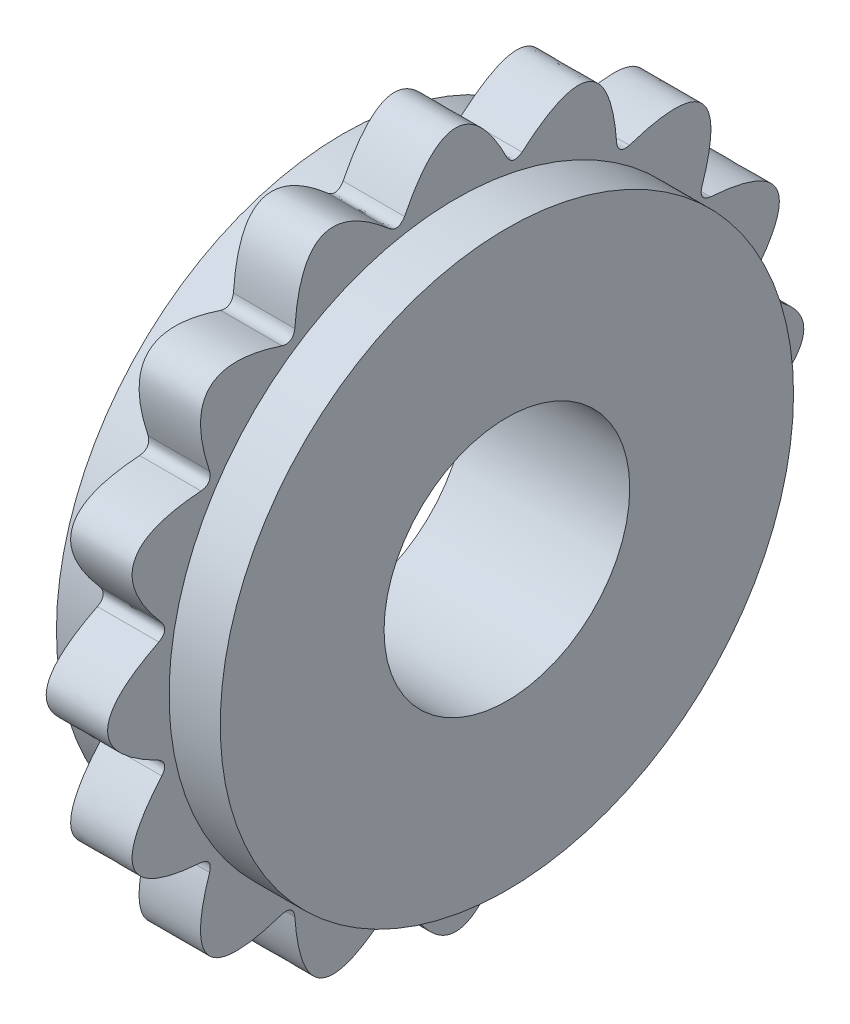
SolidWorks part; units mm, degrees
ref_plane "Front Plane" through (0, 0, 0) normal (0, 0, 1) x (1, 0, 0)
ref_plane "Top Plane" through (0, 0, 0) normal (0, 1, 0) x (1, 0, 0)
ref_plane "Right Plane" through (0, 0, 0) normal (1, 0, 0) x (0, 0, -1)
sketch "Sketch1" plane through (0, 0, 0) normal (1, 0, 0) x (0, 0, -1)
  line L0 (0, 14.5) -> (0, 17) construction
  line L1 (0, 14.5) -> (2.5, 14.5) construction
  line L2 (0, 14.5) -> (-2.5, 14.5) construction
  circle A0 centre (0, 0) radius 14.5
  spline S0 degree 2 poles (-2.5, 14.5) (0, 19.5) (2.5, 14.5) knots 0 0 0 1 1 1
  spline S1 degree 2 poles (3.2392, 14.353) (7.4623, 18.0157) (7.8586, 12.4395) knots 0 0 0 1 1 1
  spline S2 degree 2 poles (8.4853, 12.0208) (13.7886, 13.7886) (12.0208, 8.4853) knots 0 0 0 1 1 1
  spline S3 degree 2 poles (12.4395, 7.8586) (18.0157, 7.4623) (14.353, 3.2392) knots 0 0 0 1 1 1
  spline S4 degree 2 poles (14.5, 2.5) (19.5, 0) (14.5, -2.5) knots 0 0 0 1 1 1
  spline S5 degree 2 poles (14.353, -3.2392) (18.0157, -7.4623) (12.4395, -7.8586) knots 0 0 0 1 1 1
  spline S6 degree 2 poles (12.0208, -8.4853) (13.7886, -13.7886) (8.4853, -12.0208) knots 0 0 0 1 1 1
  spline S7 degree 2 poles (7.8586, -12.4395) (7.4623, -18.0157) (3.2392, -14.353) knots 0 0 0 1 1 1
  spline S8 degree 2 poles (2.5, -14.5) (0, -19.5) (-2.5, -14.5) knots 0 0 0 1 1 1
  spline S9 degree 2 poles (-3.2392, -14.353) (-7.4623, -18.0157) (-7.8586, -12.4395) knots 0 0 0 1 1 1
  spline S10 degree 2 poles (-8.4853, -12.0208) (-13.7886, -13.7886) (-12.0208, -8.4853) knots 0 0 0 1 1 1
  spline S11 degree 2 poles (-12.4395, -7.8586) (-18.0157, -7.4623) (-14.353, -3.2392) knots 0 0 0 1 1 1
  spline S12 degree 2 poles (-14.5, -2.5) (-19.5, 0) (-14.5, 2.5) knots 0 0 0 1 1 1
  spline S13 degree 2 poles (-14.353, 3.2392) (-18.0157, 7.4623) (-12.4395, 7.8586) knots 0 0 0 1 1 1
  spline S14 degree 2 poles (-12.0208, 8.4853) (-13.7886, 13.7886) (-8.4853, 12.0208) knots 0 0 0 1 1 1
  spline S15 degree 2 poles (-7.8586, 12.4395) (-7.4623, 18.0157) (-3.2392, 14.353) knots 0 0 0 1 1 1
  spline S16 degree 2 poles (-3.2392, 14.353) (-2.8043, 14.0107) (-2.5, 14.5) knots 0 0 0 1 1 1
  spline S17 degree 2 poles (2.5, 14.5) (2.7708, 14.0174) (3.2392, 14.353) knots 0 0 0 1 1 1
  spline S18 degree 2 poles (7.8586, 12.4395) (7.9241, 11.89) (8.4853, 12.0208) knots 0 0 0 1 1 1
  spline S19 degree 2 poles (12.0208, 8.4853) (11.871, 7.9525) (12.4395, 7.8586) knots 0 0 0 1 1 1
  spline S20 degree 2 poles (14.353, 3.2392) (14.0107, 2.8043) (14.5, 2.5) knots 0 0 0 1 1 1
  spline S21 degree 2 poles (14.5, -2.5) (14.0174, -2.7708) (14.353, -3.2392) knots 0 0 0 1 1 1
  spline S22 degree 2 poles (12.4395, -7.8586) (11.89, -7.9241) (12.0208, -8.4853) knots 0 0 0 1 1 1
  spline S23 degree 2 poles (8.4853, -12.0208) (7.9525, -11.871) (7.8586, -12.4395) knots 0 0 0 1 1 1
  spline S24 degree 2 poles (3.2392, -14.353) (2.8043, -14.0107) (2.5, -14.5) knots 0 0 0 1 1 1
  spline S25 degree 2 poles (-2.5, -14.5) (-2.7708, -14.0174) (-3.2392, -14.353) knots 0 0 0 1 1 1
  spline S26 degree 2 poles (-7.8586, -12.4395) (-7.9241, -11.89) (-8.4853, -12.0208) knots 0 0 0 1 1 1
  spline S27 degree 2 poles (-12.0208, -8.4853) (-11.871, -7.9525) (-12.4395, -7.8586) knots 0 0 0 1 1 1
  spline S28 degree 2 poles (-14.353, -3.2392) (-14.0107, -2.8043) (-14.5, -2.5) knots 0 0 0 1 1 1
  spline S29 degree 2 poles (-14.5, 2.5) (-14.0174, 2.7708) (-14.353, 3.2392) knots 0 0 0 1 1 1
  spline S30 degree 2 poles (-12.4395, 7.8586) (-11.89, 7.9241) (-12.0208, 8.4853) knots 0 0 0 1 1 1
  spline S31 degree 2 poles (-8.4853, 12.0208) (-7.9525, 11.871) (-7.8586, 12.4395) knots 0 0 0 1 1 1
  point P57 (0, 0)
  point P103 (0, 0)
  dimension "D2" = 29
  dimension "D3" = 2.5
  dimension "D4" = 2.5
extrude "Boss-Extrude1" add sketch "Sketch1" along normal blind 3 contours S31 A0 S30 S29 S28 S27 S26 S25 S24 S23 S22 S21 S20 S19 S18 S17 S16 | S19 S2 S18 A0 | S20 S3 S19 A0 | S21 S4 S20 A0 | S22 S5 S21 A0 | S18 S1 S17 A0 | S17 S0 S16 A0 | S31 S14 S30 A0 | S30 S13 S29 A0 | S29 S12 S28 A0 | S28 S11 S27 A0 | S27 S10 S26 A0 | S26 S9 S25 A0 | S25 S8 S24 A0 | S24 S7 S23 A0 | S23 S6 S22 A0 | S31 A0 S16 S15
sketch "Sketch2" plane through (0, 0, 0) normal (-1, 0, 0) x (0, 0, 1)
  circle A0 centre (0, 0) radius 14
extrude "Boss-Extrude2" add sketch "Sketch2" along normal blind 2.5
sketch "Sketch3" plane through (3, 0, 0) normal (1, 0, 0) x (0, 0, -1)
  circle A0 centre (0, 0) radius 14
extrude "Boss-Extrude3" add sketch "Sketch3" along normal blind 2.5
sketch "Sketch4" plane through (5.5, 0, 0) normal (1, 0, 0) x (0, 0, -1)
  circle A0 centre (0, 0) radius 6
extrude "Cut-Extrude1" cut sketch "Sketch4" against normal blind 22.5
